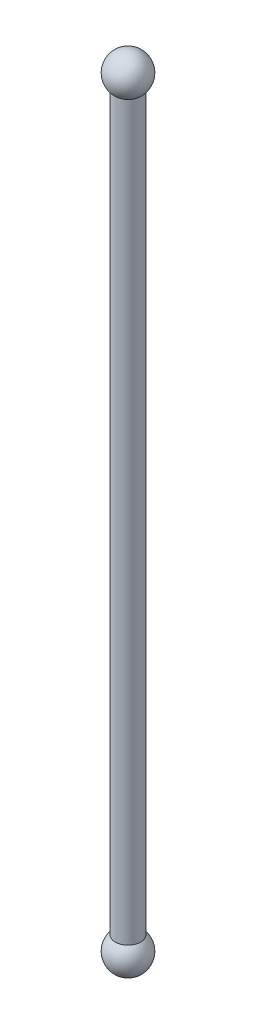
SolidWorks part; units mm, degrees
ref_plane "前视基准面" through (0, 0, 0) normal (0, 0, 1) x (1, 0, 0)
ref_plane "上视基准面" through (0, 0, 0) normal (0, 1, 0) x (1, 0, 0)
ref_plane "右视基准面" through (0, 0, 0) normal (1, 0, 0) x (0, 0, -1)
sketch "草图2" plane through (0, 0, 0) normal (0, 1, 0) x (1, 0, 0)
  circle A0 centre (0, 0) radius 5
  dimension "D1" = 10
extrude "凸台-拉伸1" add sketch "草图2" along normal mid plane 300
sketch "草图3" plane through (0, 0, 0) normal (0, 0, 1) x (1, 0, 0)
  line L0 (5, 150) -> (-5, 150) construction
  line L1 (0, 157.5) -> (0, 142.5)
  arc A0 (0, 142.5) -> (0, 157.5) centre (0, 150) ccw
  dimension "D1" = 15
revolve "旋转1" add sketch "草图3" angle 360 about L1
mirror "镜向1" about plane through (0, 0, 0) normal (0, 1, 0) of "旋转1"
